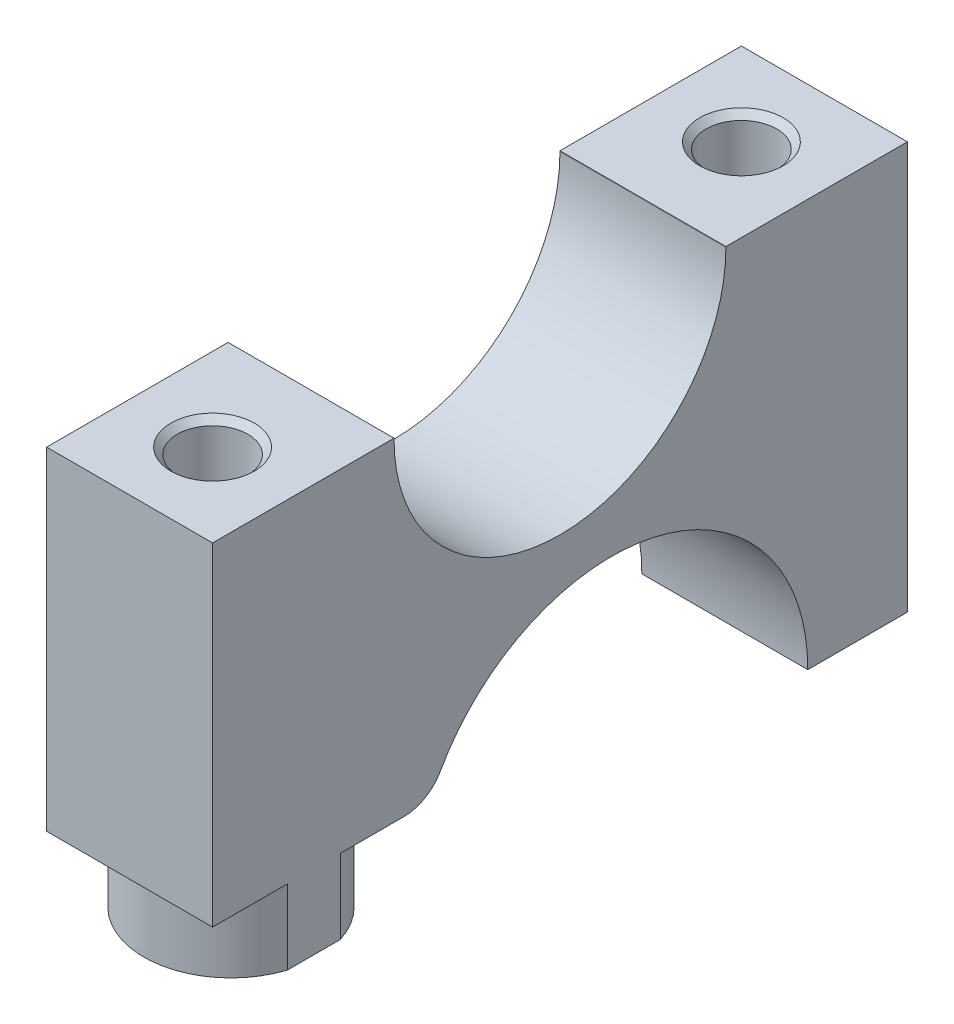
SolidWorks part; units mm, degrees
material "2014 Alloy"
ref_plane "Front Plane" through (0, 0, 0) normal (0, 0, 1) x (1, 0, 0)
ref_plane "Top Plane" through (0, 0, 0) normal (0, 1, 0) x (1, 0, 0)
ref_plane "Right Plane" through (0, 0, 0) normal (1, 0, 0) x (0, 0, -1)
sketch "Sketch1" plane through (0, 0, 0) normal (1, 0, 0) x (0, 0, -1)
  line L0 (-35.65, 0) -> (35.65, 0)
  line L1 (35.65, 0) -> (35.65, -49.098)
  line L2 (35.65, -49.098) -> (23.65, -49.098)
  line L3 (0, 0) -> (0, -49.098) construction
  line L4 (-35.65, -49.098) -> (-23.65, -49.098)
  line L5 (-35.65, 0) -> (-35.65, -49.098) construction
  line L6 (-35.65, -49.098) -> (-48.09, -49.098)
  line L7 (-48.09, -49.098) -> (-48.09, 0)
  line L8 (-48.09, 0) -> (-35.65, 0)
  line L9 (-35.87, -49.098) -> (-35.87, -46.7861) construction
  arc A0 (23.65, -49.098) -> (-23.65, -49.098) centre (0, -49.098) ccw
  point P9 (-35.87, -49.098)
  dimension "D1" = 23.65
  dimension "D2" = 12
  dimension "D3" = 49.098
  dimension "D4" = 35.87
extrude "Boss-Extrude1" add sketch "Sketch1" along normal blind 20
hole_wizard "M10 Tapped Hole1" positions "Sketch3" profile "Sketch2" tap size "M10" standard "ISO"
sketch "Sketch3" plane through (0, 0, 0) normal (0, 1, 0) x (1, 0, 0)
  line L0 (10, -48.09) -> (10, -38.09) construction
  line L2 (10, -38.09) -> (10, 25.65) construction
  line L3 (10, 25.65) -> (10, 35.65) construction
  line L4 (20, 35.65) -> (0, 35.65) construction
  line L6 (20, 35.65) -> (20, -48.09) construction
  line L7 (20, 25.65) -> (10, 25.65) construction
  line L8 (20, -48.09) -> (0, -48.09) construction
  point P0 (10, -38.09)
  point P2 (10, 25.65)
sketch "Sketch2" plane through (10, 0, 38.09) normal (1, 0, 0) x (0, 0, 1)
  line L0 (0, 0) -> (0, 30.0537)
  line L1 (0, 30.0537) -> (4.25, 27.5)
  line L2 (4.25, 27.5) -> (4.25, 0.775)
  line L3 (4.25, 0.775) -> (5.025, 0)
  line L5 (5.025, 0) -> (0, 0)
  line L6 (-4.25, 0.775) -> (-5.025, 0) construction
  line L10 (0, 30.0537) -> (-4.25, 27.5) construction
  line L11 (0, -6.35) -> (0, 107.95) construction
  dimension "Tap Drill Dia." = 8.5
  dimension "Tap Drill Depth" = 27.5
  dimension "Near C'Sink Dia." = 10.05
  dimension "Near C'Sink Angle" = 90
  dimension "Drill Angle" = 118
hole_wizard "M8 Tapped Hole1" positions "Sketch5" profile "Sketch4" tap size "M8" standard "ISO"
sketch "Sketch5" plane through (0, -49.098, 0) normal (0, -1, 0) x (-1, 0, 0)
  line L0 (-10, -48.09) -> (-10, -23.65) construction
  line L2 (-20, -23.65) -> (0, -23.65) construction
  line L4 (-10, 23.65) -> (-10, 35.65) construction
  line L5 (-20, 23.65) -> (0, 23.65) construction
  line L6 (-20, 35.65) -> (0, 35.65) construction
  line L7 (-20, -48.09) -> (0, -48.09) construction
  point P0 (-10, -35.87)
  point P2 (-10, 29.65)
sketch "Sketch4" plane through (10, -49.098, 35.87) normal (1, 0, 0) x (0, 0, -1)
  line L0 (0, 0) -> (0, 24.2929)
  line L1 (0, 24.2929) -> (3.4, 22.25)
  line L2 (3.4, 22.25) -> (3.4, 0.625)
  line L3 (3.4, 0.625) -> (4.025, 0)
  line L5 (4.025, 0) -> (0, 0)
  line L6 (-3.4, 0.625) -> (-4.025, 0) construction
  line L10 (0, 24.2929) -> (-3.4, 22.25) construction
  line L11 (0, -6.35) -> (0, 107.95) construction
  dimension "Tap Drill Dia." = 6.8
  dimension "Tap Drill Depth" = 22.25
  dimension "Near C'Sink Dia." = 8.05
  dimension "Near C'Sink Angle" = 90
  dimension "Drill Angle" = 118
sketch "Sketch6" plane through (20, 0, 0) normal (1, 0, 0) x (0, 0, -1)
  line L0 (-6.22, 0.1) -> (-6.22, -0.1) construction
  line L1 (35.65, 0) -> (-48.09, 0) construction
  line L2 (13.78, 0.1) -> (13.78, -0.1)
  line L3 (-26.22, 0.1) -> (-26.22, -0.1)
  arc A0 (13.78, 0.1) -> (-26.22, 0.1) centre (-6.22, 0.1) ccw
  arc A1 (-26.22, -0.1) -> (13.78, -0.1) centre (-6.22, -0.1) ccw
  point P4 (-6.22, 0)
  dimension "D1" = 20
  dimension "D2" = 0.2
extrude "Cut-Extrude1" cut sketch "Sketch6" against normal through all
sketch "Sketch7" plane through (0, -49.098, 0) normal (0, -1, 0) x (1, 0, 0)
  circle A0 centre (10, 35.87) radius 10.5
  circle A1 centre (10, 35.87) radius 3.4 construction
  circle A2 centre (10, 35.87) radius 21.4489
  dimension "D1" = 21
extrude "Cut-Extrude2" cut sketch "Sketch7" against normal blind 9
fillet "Fillet1" radius 5 1 edges at (10, -40.098, 21.8706)
sketch "Sketch8" [suppressed] plane through (0, 0, 0) normal (-1, 0, 0) x (0, 0, 1)
  line L8 (-12.68, -0.1) -> (-12.68, 1)
  line L9 (-12.68, 1) -> (-36.55, 1)
  line L10 (-36.55, 1) -> (-36.55, -50.12)
  line L11 (-36.55, -50.12) -> (-22.5278, -50.12)
  line L12 (22.5278, -50.12) -> (49.19, -50.12)
  line L13 (49.19, -50.12) -> (49.19, 1)
  line L14 (49.19, 1) -> (25.32, 1)
  line L15 (25.32, 1) -> (25.32, -0.1)
  line L16 (-13.68, -0.1) -> (-13.68, 0)
  line L17 (-13.68, 0) -> (-35.55, 0)
  line L18 (-35.55, 0) -> (-35.55, -49.12)
  line L19 (-35.55, -49.12) -> (-23.55, -49.12)
  line L20 (23.55, -49.12) -> (48.19, -49.12)
  line L21 (48.19, -49.12) -> (48.19, 0)
  line L22 (48.19, 0) -> (26.32, 0)
  line L23 (26.32, 0) -> (26.32, -0.1)
  line L24 (-13.68, -0.1) -> (-13.68, 0) construction
  line L25 (-13.68, 0) -> (-35.55, 0) construction
  line L26 (-35.55, 0) -> (-35.55, -49.12) construction
  line L27 (-35.55, -49.12) -> (-23.55, -49.12) construction
  line L28 (23.55, -49.12) -> (48.19, -49.12) construction
  line L29 (48.19, -49.12) -> (48.19, 0) construction
  line L30 (48.19, 0) -> (26.32, 0) construction
  line L31 (26.32, 0) -> (26.32, -0.1) construction
  arc A2 (22.5278, -50.12) -> (-22.5278, -50.12) centre (0, -49.12) ccw
  arc A3 (-12.68, -0.1) -> (25.32, -0.1) centre (6.32, -0.1) ccw
  arc A4 (-13.68, -0.1) -> (26.32, -0.1) centre (6.32, -0.1) ccw
  arc A5 (23.55, -49.12) -> (-23.55, -49.12) centre (0, -49.12) ccw
  arc A6 (-13.68, -0.1) -> (26.32, -0.1) centre (6.32, -0.1) ccw construction
  arc A7 (23.55, -49.12) -> (-23.55, -49.12) centre (0, -49.12) ccw construction
  dimension "D1" = 0
  dimension "D2" = 1
extrude "Boss-Extrude2" [suppressed] add sketch "Sketch8" against normal blind 25
